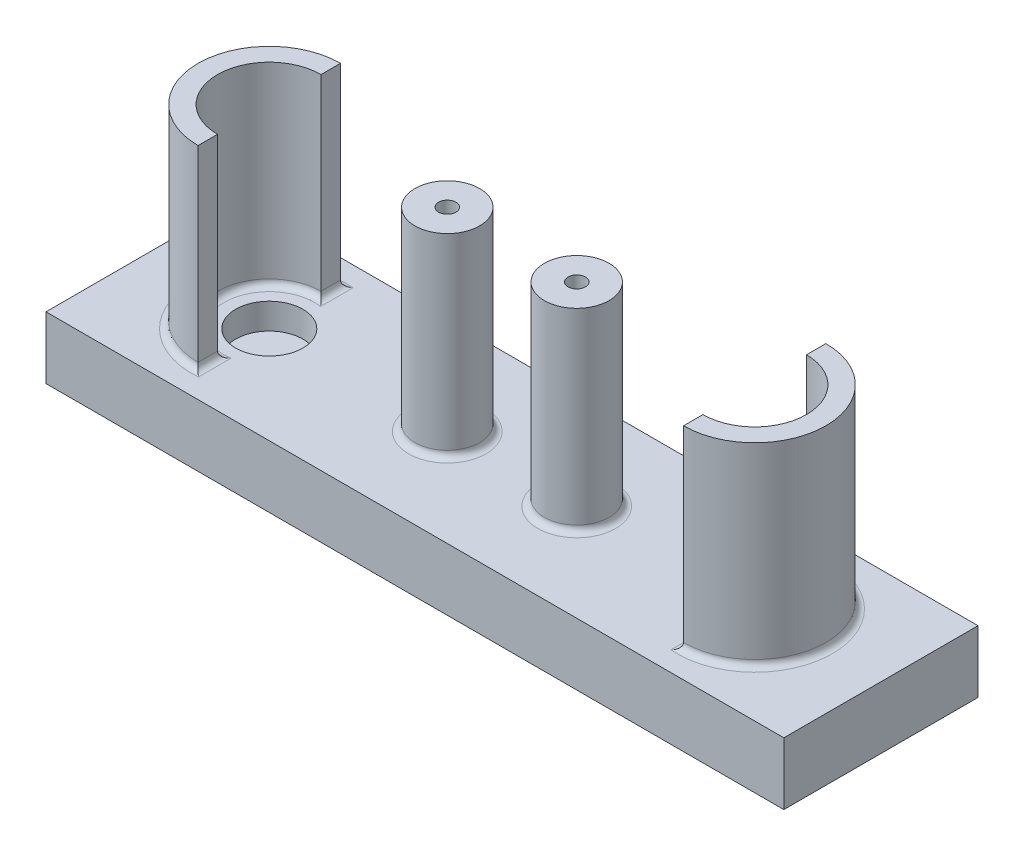
SolidWorks part; units mm, degrees
ref_plane "Front Plane" through (0, 0, 0) normal (0, 0, 1) x (1, 0, 0)
ref_plane "Top Plane" through (0, 0, 0) normal (0, 1, 0) x (1, 0, 0)
ref_plane "Right Plane" through (0, 0, 0) normal (1, 0, 0) x (0, 0, -1)
sketch "Sketch1" plane through (0, 0, 0) normal (0, 1, 0) x (1, 0, 0)
  line L0 (72.39, 38.1) -> (72.39, 0) construction
  line L1 (0, 0) -> (144.78, 0)
  line L2 (0, 0) -> (0, 38.1)
  line L3 (0, 38.1) -> (144.78, 38.1)
  line L4 (144.78, 0) -> (144.78, 38.1)
  line L5 (59.69, 19.05) -> (72.39, 19.05) construction
  line L6 (72.39, 19.05) -> (85.09, 19.05) construction
  circle A0 centre (59.69, 19.05) radius 1.7
  circle A1 centre (85.09, 19.05) radius 1.7
  dimension "D3" = 3.4
  dimension "D1" = 38.1
  dimension "D2" = 144.78
  dimension "D4" = 12.7
extrude "Boss-Extrude1" add sketch "Sketch1" along normal blind 12.7
sketch "Sketch2" plane through (0, 12.7, 0) normal (0, 1, 0) x (1, 0, 0)
  line L0 (72.39, 38.1) -> (72.39, 0) construction
  line L1 (144.78, 38.1) -> (0, 38.1) construction
  line L2 (0, 0) -> (144.78, 0) construction
  circle A0 centre (24.765, 19.05) radius 6.6
  circle A2 centre (120.015, 19.05) radius 6.6
  point P10 (72.39, 19.05)
  dimension "D1" = 95.25
  dimension "D2" = 13.2
extrude "Cut-Extrude1" cut sketch "Sketch2" against normal blind 5.08
sketch "Sketch4" plane through (0, 12.7, 0) normal (0, 1, 0) x (1, 0, 0)
  line L0 (72.39, 38.1) -> (72.39, 0) construction
  line L1 (144.78, 38.1) -> (0, 38.1) construction
  line L2 (0, 0) -> (144.78, 0) construction
  line L3 (24.765, 33.02) -> (24.765, 29.21)
  line L4 (24.765, 8.89) -> (24.765, 5.08)
  line L5 (120.015, 8.89) -> (120.015, 5.08)
  line L6 (120.015, 33.02) -> (120.015, 29.21)
  arc A1 (24.765, 33.02) -> (24.765, 5.08) centre (24.765, 19.05) ccw
  circle A3 centre (85.09, 19.05) radius 6.35
  circle A4 centre (59.69, 19.05) radius 6.35
  arc A5 (24.765, 29.21) -> (24.765, 8.89) centre (24.765, 19.05) ccw
  arc A6 (120.015, 29.21) -> (120.015, 8.89) centre (120.015, 19.05) cw
  arc A7 (120.015, 33.02) -> (120.015, 5.08) centre (120.015, 19.05) cw
  circle A8 centre (85.09, 19.05) radius 1.7 construction
  circle A9 centre (59.69, 19.05) radius 1.7 construction
  circle A10 centre (85.09, 19.05) radius 1.7
  circle A11 centre (59.69, 19.05) radius 1.7
  point P11 (72.39, 19.05)
  dimension "D2" = 12.7
  dimension "D1" = 25.4
  dimension "D4" = 10.16
  dimension "D3" = 3.81
extrude "Boss-Extrude2" add sketch "Sketch4" along normal blind 38.1
fillet "Fillet1" radius 1.27 10 edges at (120.015, 12.7, -31.115) (130.175, 12.7, -19.05) (120.015, 12.7, -6.985) (133.985, 12.7, -19.05) (24.765, 12.7, -6.985) (24.765, 12.7, -31.115) (14.605, 12.7, -19.05) (10.795, 12.7, -19.05) (85.09, 12.7, -25.4) (59.69, 12.7, -25.4)
chamfer "Chamfer1" distance 0.5 angle 45 6 edges at (72.39, 0, 0) (144.78, 0, -19.05) (72.39, 0, -38.1) (0, 0, -19.05) (85.09, 0, -17.35) (59.69, 0, -17.35)
